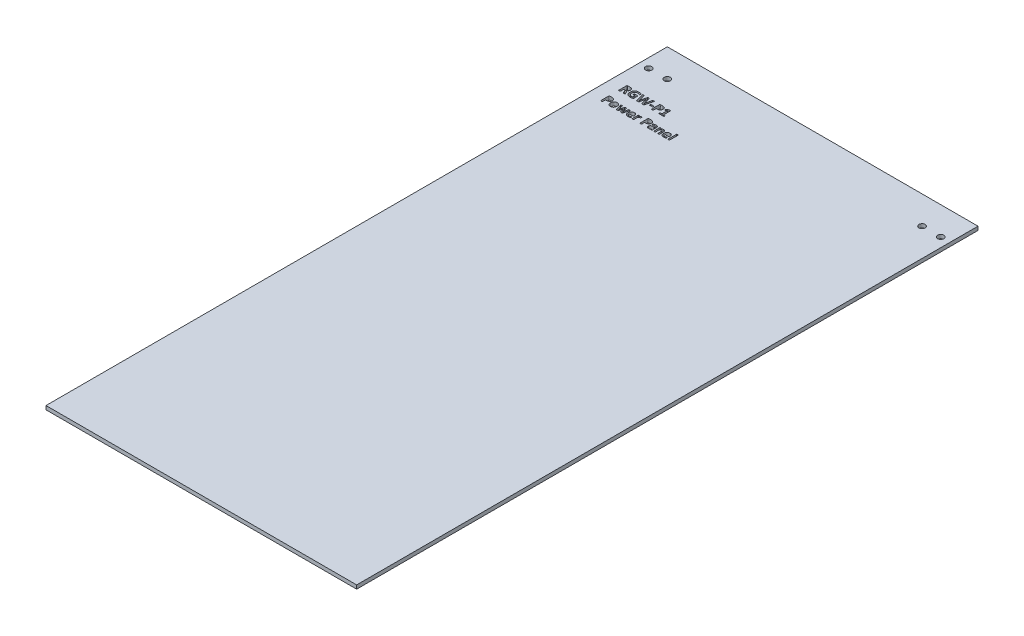
SolidWorks part; units mm, degrees
material "Клен"
ref_plane "Спереди (XY)" through (0, 0, 0) normal (0, 0, 1) x (1, 0, 0)
ref_plane "Сверху (XZ)" through (0, 0, 0) normal (0, 1, 0) x (1, 0, 0)
ref_plane "Справа (ZY)" through (0, 0, 0) normal (1, 0, 0) x (0, 0, -1)
sketch "Эскиз1" plane through (0, 0, 0) normal (0, 1, 0) x (1, 0, 0)
  line L1 (125, -250) -> (-125, -250)
  line L2 (125, -250) -> (125, 250)
  line L3 (125, 250) -> (-125, 250)
  line L4 (-125, -250) -> (-125, 250)
  line L5 (125, -250) -> (-125, 250) construction
  line L6 (125, 250) -> (-125, -250) construction
  point P0 (0, 0)
  dimension "D1" = 500
  dimension "D2" = 250
extrude "Бобышка-Вытянуть1" add sketch "Эскиз1" along normal blind 3
sketch "Эскиз3" plane through (0, 3, 0) normal (0, 1, 0) x (1, 0, 0)
  line L0 (-125, 250) -> (-125, -250) construction
  line L1 (125, 250) -> (-125, 250) construction
  line L3 (125, -250) -> (125, 250) construction
  circle A0 centre (-117.5, 227.5) radius 2.5
  circle A1 centre (-102.5, 227.5) radius 2.5
  circle A2 centre (117.5, 227.5) radius 2.5
  circle A3 centre (102.5, 227.5) radius 2.5
  dimension "D1" = 5
  dimension "D4" = 5
  dimension "D5" = 15
  dimension "D6" = 5
  dimension "D7" = 5
  dimension "D2" = 7.5
  dimension "D3" = 22.5
  dimension "D8" = 7.5
  dimension "D9" = 22.5
  dimension "D10" = 15
extrude "Вырез-Вытянуть2" cut sketch "Эскиз3" against normal blind 3
sketch "Эскиз4" plane through (0, 3, 0) normal (0, 1, 0) x (1, 0, 0)
  line L0 (-125, 250) -> (-125, -250) construction
  line L2 (125, 250) -> (-125, 250) construction
  text T0 "RGW-P1\r\nPower Panel" font "Calibri" height in points 26
  point P5 (-113.9291, 250)
  dimension "D1" = 10
  dimension "D2" = 50
extrude "Вырез-Вытянуть3" cut sketch "Эскиз4" against normal blind 10
